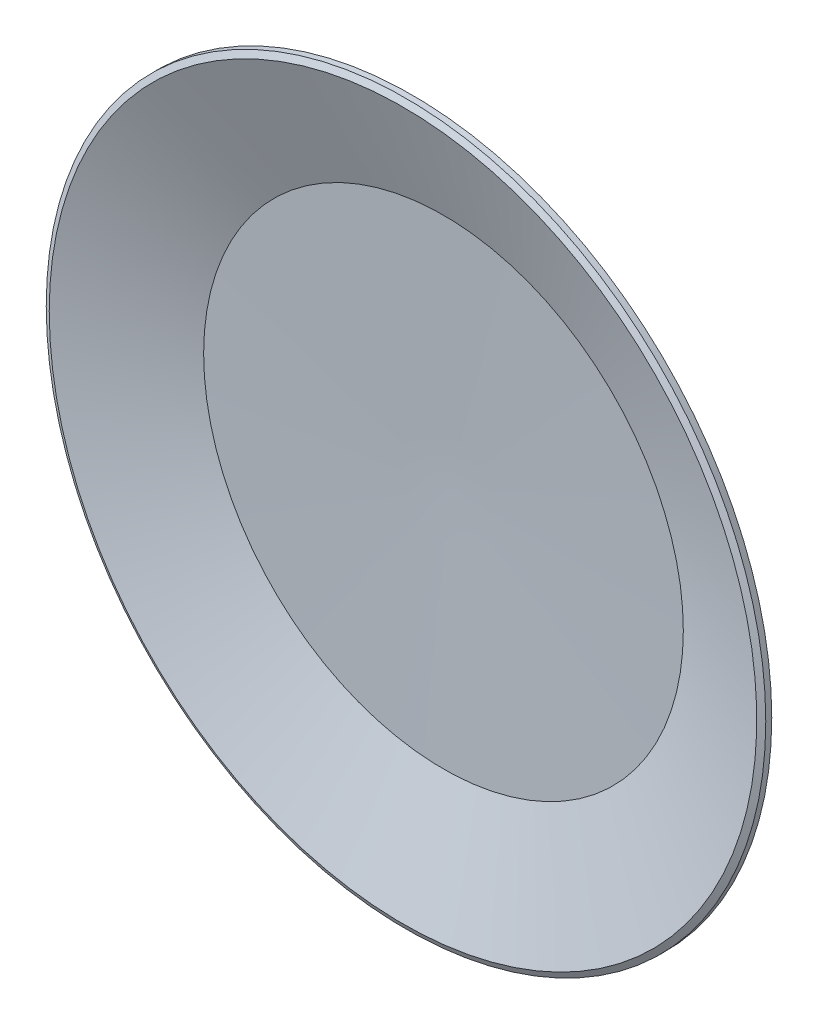
SolidWorks part; units mm, degrees
ref_plane "Front Plane" through (0, 0, 0) normal (1, 0, 0) x (0, 1, 0)
ref_plane "Top Plane" through (0, 0, 0) normal (0, 0, 1) x (0, 1, 0)
ref_plane "Right Plane" through (0, 0, 0) normal (0, 1, 0) x (-1, 0, 0)
sketch "Sketch1" plane through (0, 0, 0) normal (0, 1, 0) x (-1, 0, 0)
  line L0 (0, 2) -> (-66, 2)
  line L1 (-66, 2) -> (-68, 0)
  line L2 (-68, 0) -> (-72, 0)
  line L3 (-72, 0) -> (-74, 2.5)
  line L4 (-74, 2.5) -> (-82, 5)
  line L5 (-82, 5) -> (-120, 19)
  line L6 (-120, 19) -> (-120, 21)
  line L7 (-120, 21) -> (-118, 22)
  line L8 (-118, 22) -> (-80, 8.5)
  line L9 (-80, 8.5) -> (0, 6.5)
  line L10 (0, 6.5) -> (0, 2)
  line L11 (0, -500) -> (0, 500) construction
revolve "Revolve1" add sketch "Sketch1" angle 360 about L11
